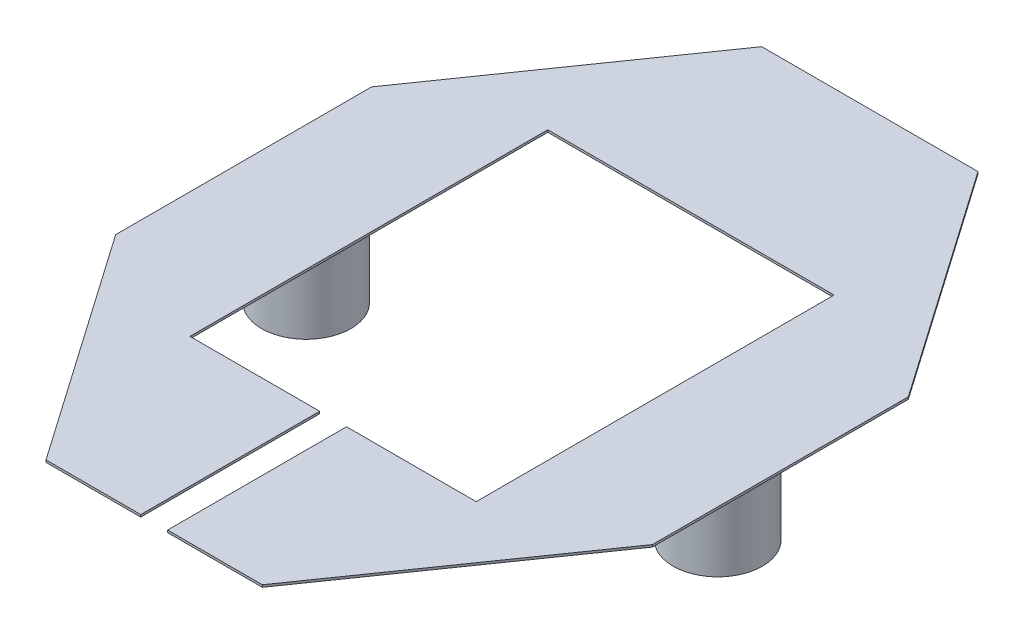
SolidWorks part; units mm, degrees
ref_plane "Front Plane" through (0, 0, 0) normal (0, 0, 1) x (1, 0, 0)
ref_plane "Top Plane" through (0, 0, 0) normal (0, 1, 0) x (1, 0, 0)
ref_plane "Right Plane" through (0, 0, 0) normal (1, 0, 0) x (0, 0, -1)
sketch "Sketch1" plane through (0, 0, 0) normal (0, 1, 0) x (1, 0, 0)
  line L0 (-16.5, 21.5) -> (16.5, 21.5)
  line L5 (16.5, 21.5) -> (16.5, -21.5)
  line L6 (-16.5, -21.5) -> (16.5, -21.5)
  line L7 (-16.5, 21.5) -> (-16.5, -21.5)
extrude "Boss-Extrude1" add sketch "Sketch1" along normal blind 0.375
sketch "Sketch2" plane through (0, 0, 0) normal (0, -1, 0) x (1, 0, 0)
  line L0 (5, 21.5) -> (16.5, 21.5)
  line L1 (16.5, -5) -> (16.5, -21.5)
  line L2 (-5, -21.5) -> (-16.5, -21.5)
  line L3 (-16.5, 5) -> (-16.5, 21.5)
  line L8 (-5, -20) -> (-5, -21.5)
  line L9 (5, -20) -> (5, -21.5)
  line L10 (-16.5, 21.5) -> (16.5, 21.5) construction
  line L11 (15, -5) -> (16.5, -5)
  line L12 (-16.5, -21.5) -> (-16.5, 21.5) construction
  line L13 (16.5, 21.5) -> (16.5, -21.5) construction
  line L14 (15, -20) -> (15, 20)
  line L15 (-15, -20) -> (15, -20)
  line L16 (-15, 20) -> (-15, -20)
  line L17 (15, 20) -> (-15, 20)
  line L18 (15, -5) -> (15, 5)
  line L19 (-5, -20) -> (5, -20)
  line L20 (-15, 5) -> (-15, -5)
  line L21 (5, 20) -> (-5, 20)
  line L22 (16.5, -21.5) -> (-16.5, -21.5) construction
  line L23 (-16.5, 21.5) -> (-5, 21.5)
  line L24 (-16.5, -21.5) -> (-16.5, -5)
  line L25 (16.5, 21.5) -> (16.5, 5)
  line L26 (16.5, -21.5) -> (5, -21.5)
  line L27 (-5, 21.5) -> (-5, 20)
  line L28 (5, 21.5) -> (5, 20)
  line L29 (-16.5, 5) -> (-15, 5)
  line L30 (-16.5, -5) -> (-15, -5)
  line L31 (15, 5) -> (16.5, 5)
  dimension "D2" = 5
  dimension "D3" = 5
  dimension "D4" = 5
  dimension "D5" = 5
  dimension "D1" = 1.5
extrude "Cut-Extrude1" cut sketch "Sketch2" against normal blind 0.25
sketch "Sketch3" plane through (0, 0.25, 0) normal (0, -1, 0) x (1, 0, 0)
  line L1 (-8, -10) -> (8, -10)
  line L2 (-8, -10) -> (-8, 10)
  line L3 (-8, 10) -> (8, 10)
  line L4 (8, -10) -> (8, 10)
  dimension "D1" = 20
  dimension "D2" = 10
  dimension "D3" = 16
  dimension "D4" = 8
extrude "Cut-Extrude2" cut sketch "Sketch3" against normal blind 4.125
sketch "Sketch4" plane through (0, 0.25, 0) normal (0, -1, 0) x (1, 0, 0)
  line L0 (-5, 21.5) -> (-16.5, 5)
  line L1 (5, 21.5) -> (16.5, 5)
  line L2 (-16.5, -5) -> (-5, -21.5)
  line L3 (16.5, -5) -> (5, -21.5)
  line L4 (-16.5, 5) -> (-16.5, 21.5)
  line L5 (-16.5, 21.5) -> (-5, 21.5)
  line L6 (5, 21.5) -> (16.5, 21.5)
  line L7 (16.5, 21.5) -> (16.5, 5)
  line L8 (16.5, -5) -> (16.5, -21.5)
  line L9 (16.5, -21.5) -> (5, -21.5)
  line L10 (-16.5, -5) -> (-16.5, -21.5)
  line L11 (-16.5, -21.5) -> (-5, -21.5)
extrude "Cut-Extrude3" cut sketch "Sketch4" against normal blind 4.125
sketch "Sketch5" plane through (0, 0.25, 0) normal (0, -1, 0) x (1, 0, 0)
  line L0 (8, 10) -> (-8, 10) construction
  line L1 (-0.75, 10) -> (0.75, 10)
  line L2 (-0.75, 10) -> (-0.75, 20)
  line L3 (-0.75, 20) -> (0.75, 20)
  line L4 (0.75, 10) -> (0.75, 20)
  line L5 (5, 20) -> (-5, 20) construction
  dimension "D1" = 0.75
  dimension "D2" = 0.75
extrude "Cut-Extrude4" cut sketch "Sketch5" against normal blind 10
sketch "Sketch6" plane through (0, 0.25, 0) normal (0, -1, 0) x (1, 0, 0)
  line L0 (-15, 5) -> (-15, -5) construction
  line L1 (15, -5) -> (15, 5) construction
  line L2 (15, 11.1436) -> (26.6711, 11.1436)
  line L3 (15, 11.1436) -> (15, -13.8117)
  line L4 (15, -13.8117) -> (26.6711, -13.8117)
  line L5 (10.8746, -20) -> (-12.3536, -20)
  line L6 (10.8746, -20) -> (10.8746, -25.3068)
  line L7 (10.8746, -25.3068) -> (-12.3536, -25.3068)
  line L8 (-12.3536, -20) -> (-12.3536, -25.3068)
  line L9 (-5, -20) -> (5, -20) construction
  line L10 (26.6711, 11.1436) -> (26.6711, -13.8117)
  line L11 (-23.6761, 10.135) -> (-15, 10.135)
  line L12 (-23.6761, 10.135) -> (-23.6761, -12.2615)
  line L13 (-23.6761, -12.2615) -> (-15, -12.2615)
  line L14 (-15, 10.135) -> (-15, -12.2615)
  line L15 (-14.7988, 25.8046) -> (12.9232, 25.8046)
  line L16 (-14.7988, 25.8046) -> (-14.7988, 20)
  line L17 (-14.7988, 20) -> (12.9232, 20)
  line L18 (12.9232, 25.8046) -> (12.9232, 20)
  line L19 (5, 20) -> (-5, 20) construction
  dimension "D1" = 0
  dimension "D2" = 0
  dimension "D3" = 0
  dimension "D4" = 0
extrude "Cut-Extrude5" cut sketch "Sketch6" against normal mid plane 10
sketch "Sketch7" plane through (0, 0.25, 0) normal (0, -1, 0) x (-1, 0, 0)
  circle A0 centre (11.5, 0) radius 2.5
  circle A1 centre (-11.5, 0) radius 2.5
  circle A2 centre (11.5, 0) radius 1.5
  circle A3 centre (-11.5, 0) radius 1.5
  dimension "D1" = 11.5
  dimension "D3" = 5
  dimension "D2" = 11.5
extrude "Boss-Extrude2" add sketch "Sketch7" along normal blind 5
